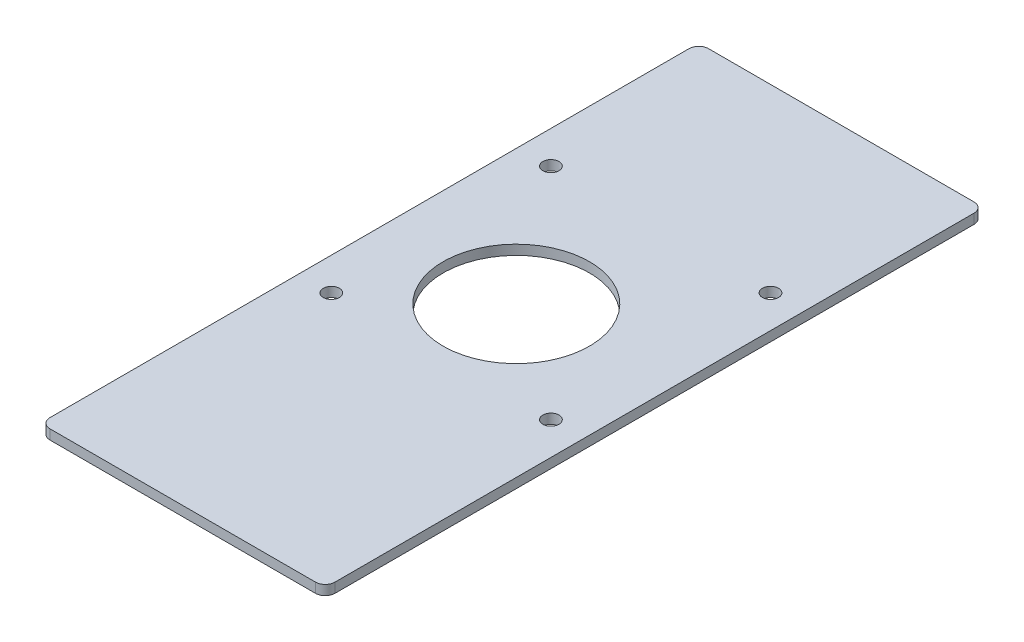
SolidWorks part; units mm, degrees
ref_plane "Front Plane" through (0, 0, 0) normal (0, 0, 1) x (1, 0, 0)
ref_plane "Top Plane" through (0, 0, 0) normal (0, 1, 0) x (1, 0, 0)
ref_plane "Right Plane" through (0, 0, 0) normal (1, 0, 0) x (0, 0, -1)
sketch "Sketch1" plane through (0, 0, 0) normal (0, 1, 0) x (1, 0, 0)
  line L0 (-14.4901, 44.9598) -> (10.7099, 44.9598) construction
  line L1 (-45.6901, 44.9598) -> (-20.4901, 44.9598) construction
  line L2 (-45.6901, 44.9598) -> (-45.6901, -10.6402) construction
  line L3 (-45.6901, -10.6402) -> (-20.4901, -10.6402) construction
  line L4 (-20.4901, 44.9598) -> (-20.4901, -10.6402) construction
  line L5 (-14.4901, 44.9598) -> (-14.4901, -10.6402) construction
  line L6 (-14.4901, -10.6402) -> (10.7099, -10.6402) construction
  line L7 (10.7099, 44.9598) -> (10.7099, -10.6402) construction
  line L8 (-14.4901, -32.1402) -> (10.7099, -32.1402) construction
  line L9 (-45.6901, -32.1402) -> (-20.4901, -32.1402) construction
  line L10 (-45.6901, -32.1402) -> (-45.6901, -87.7402) construction
  line L11 (-45.6901, -87.7402) -> (-20.4901, -87.7402) construction
  line L12 (-20.4901, -32.1402) -> (-20.4901, -87.7402) construction
  line L13 (-14.4901, -32.1402) -> (-14.4901, -87.7402) construction
  line L14 (-14.4901, -87.7402) -> (10.7099, -87.7402) construction
  line L15 (10.7099, -32.1402) -> (10.7099, -87.7402) construction
  line L17 (-46.6901, 45.7098) -> (11.7099, 45.7098)
  line L18 (-46.6901, 45.7098) -> (-46.6901, -89.2402)
  line L19 (-46.6901, -89.2402) -> (11.7099, -89.2402)
  line L20 (11.7099, 45.7098) -> (11.7099, -89.2402)
  dimension "D1" = 25.2
  dimension "D2" = 55.6
  dimension "D3" = 25.2
  dimension "D4" = 55.6
  dimension "D5" = 25.2
  dimension "D6" = 25.2
  dimension "D7" = 55.6
  dimension "D8" = 21.5
  dimension "D9" = 6
  dimension "D10" = 6
  dimension "D11" = 1
  dimension "D12" = 1
  dimension "D13" = 1.5
  dimension "D14" = 55.6
  dimension "D15" = 1.5
extrude "Boss-Extrude1" add sketch "Sketch1" along normal blind 2
fillet "Fillet1" radius 2 4 edges at (11.7099, 1, -45.7098) (-46.6901, 1, -45.7098) (11.7099, 1, 89.2402) (-46.6901, 1, 89.2402)
sketch "Sketch2" plane through (0, 2, 0) normal (0, 1, 0) x (1, 0, 0)
  line L0 (9.7099, 45.7098) -> (-44.6901, 45.7098) construction
  line L4 (-39.9901, 8.7098) -> (5.0099, 8.7098) construction
  line L5 (-39.9901, 8.7098) -> (-39.9901, -36.2902) construction
  line L6 (-39.9901, -36.2902) -> (5.0099, -36.2902) construction
  line L7 (5.0099, 8.7098) -> (5.0099, -36.2902) construction
  line L8 (-39.9901, 8.7098) -> (5.0099, -36.2902) construction
  line L9 (-39.9901, -36.2902) -> (5.0099, 8.7098) construction
  circle A0 centre (-39.9901, 8.7098) radius 1.65
  circle A1 centre (5.0099, 8.7098) radius 1.65
  circle A2 centre (5.0099, -36.2902) radius 1.65
  circle A3 centre (-39.9901, -36.2902) radius 1.65
  point P6 (-17.4901, -13.7902)
  dimension "D3" = 3.3
  dimension "D1" = 45
  dimension "D2" = 45
  dimension "D4" = 37
extrude "Cut-Extrude1" cut sketch "Sketch2" against normal through all
sketch "Sketch3" plane through (0, 2, 0) normal (0, 1, 0) x (1, 0, 0)
  line L0 (9.7099, 45.7098) -> (-44.6901, 45.7098) construction
  circle A0 centre (-19.0845, -19.2902) radius 15
  dimension "D1" = 30
  dimension "D2" = 65
extrude "Cut-Extrude2" cut sketch "Sketch3" against normal through all
